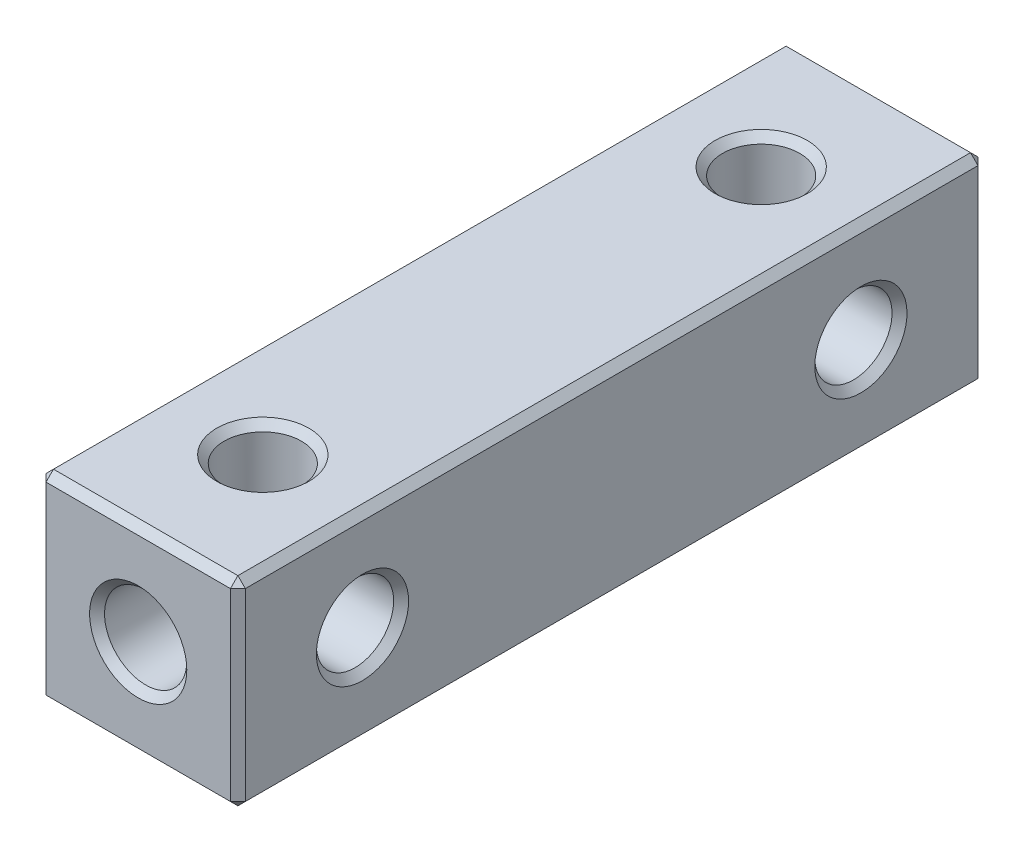
SolidWorks part; units mm, degrees
ref_plane "前视基准面" through (0, 0, 0) normal (0, 0, 1) x (1, 0, 0)
ref_plane "上视基准面" through (0, 0, 0) normal (0, 1, 0) x (1, 0, 0)
ref_plane "右视基准面" through (0, 0, 0) normal (1, 0, 0) x (0, 0, -1)
sketch "草图1" plane through (0, 0, 0) normal (0, 0, 1) x (1, 0, 0)
  line L1 (-4, 4) -> (4, 4)
  line L2 (-4, 4) -> (-4, -4)
  line L3 (-4, -4) -> (4, -4)
  line L4 (4, 4) -> (4, -4)
  line L5 (-4, 4) -> (4, -4) construction
  line L6 (-4, -4) -> (4, 4) construction
  point P0 (0, 0)
  dimension "D1" = 8
extrude "凸台-拉伸1" add sketch "草图1" along normal mid plane 30
hole_wizard "Ø3.1 (3.1) 直径孔1" positions "草图2" profile "草图3" hole size "Ø3.1" standard "GB" end condition through all
sketch "草图2" plane through (4, 0, 0) normal (1, 0, 0) x (0, 0, -1)
  line L0 (0, 0) -> (0, 50000) construction
  line L1 (-15, 4) -> (15, 4) construction
  line L2 (0, 0) -> (50000, 0) construction
  point P0 (-10, 0)
  point P2 (10, 0)
  point P10 (0, 4)
  point P15 (0, 0)
  point P16 (0, 0)
  dimension "D1" = 20
sketch "草图3" plane through (4, 0, 10) normal (0, 1, 0) x (0, 0, -1)
  line L0 (0, 0) -> (0, 8)
  line L1 (0, 8) -> (1.55, 8)
  line L2 (1.55, 8) -> (1.55, 0)
  line L5 (1.55, 0) -> (0, 0)
  line L11 (0, -6.35) -> (0, 107.95) construction
  dimension "通孔孔直径" = 3.1
  dimension "通孔孔深度" = 8
hole_wizard "Ø3.1 (3.1) 直径孔2" positions "草图4" profile "草图5" hole size "Ø3.1" standard "GB" end condition through all
sketch "草图4" plane through (0, 4, 0) normal (0, 1, 0) x (1, 0, 0)
  line L0 (0, 0) -> (0, 50000) construction
  line L1 (0, 0) -> (-50000, 0) construction
  point P0 (0, -10)
  point P2 (0, 10)
  point P9 (0, 0)
  point P10 (0, 0)
  point P11 (0, 0)
  dimension "D1" = 20
sketch "草图5" plane through (0, 4, 10) normal (1, 0, 0) x (0, 0, 1)
  line L0 (0, 0) -> (0, 8)
  line L1 (0, 8) -> (1.55, 8)
  line L2 (1.55, 8) -> (1.55, 0)
  line L5 (1.55, 0) -> (0, 0)
  line L11 (0, -6.35) -> (0, 107.95) construction
  dimension "通孔孔直径" = 3.1
  dimension "通孔孔深度" = 8
hole_wizard "M4 螺纹孔1" positions "草图6" profile "草图7" tap size "M4" standard "GB"
sketch "草图6" plane through (0, 0, 15) normal (0, 0, 1) x (1, 0, 0)
  point P0 (0, 0)
sketch "草图7" plane through (0, 0, 15) normal (1, 0, 0) x (0, -1, 0)
  line L0 (0, 0) -> (0, 3.45)
  line L1 (0, 3.45) -> (1.65, 3.45)
  line L2 (1.65, 3.45) -> (1.65, 0)
  line L5 (1.65, 0) -> (0, 0)
  line L11 (0, -6.35) -> (0, 107.95) construction
  dimension "通孔螺纹孔钻头直径" = 3.3
  dimension "通孔螺纹孔钻头深度" = 3.45
cosmetic thread "孔螺蚊线1" parameters "D2"=4
hole_wizard "M4 螺纹孔2" positions "草图8" profile "草图9" tap size "M4" standard "GB"
sketch "草图8" plane through (0, 0, -15) normal (0, 0, -1) x (-1, 0, 0)
  point P0 (0, 0)
sketch "草图9" plane through (0, 0, -15) normal (1, 0, 0) x (0, 1, 0)
  line L0 (0, 0) -> (0, 3.45)
  line L1 (0, 3.45) -> (1.65, 3.45)
  line L2 (1.65, 3.45) -> (1.65, 0)
  line L5 (1.65, 0) -> (0, 0)
  line L11 (0, -6.35) -> (0, 107.95) construction
  dimension "通孔螺纹孔钻头直径" = 3.3
  dimension "通孔螺纹孔钻头深度" = 3.45
cosmetic thread "孔螺蚊线2" parameters "D2"=4
chamfer "倒角1" distance 0.3 angle 45 22 edges at (-1.65, 0, -15) (1.65, 0, 15) (4, 0, -11.55) (4, 0, 8.45) (0, -4, -8.45) (0, -4, 11.55) (-4, 0, -11.55) (-4, 0, 8.45) (4, 0, 15) (4, 0, -15) (0, -4, 15) (4, -4, 0) (0, -4, -15) (-4, 0, 15) (-4, -4, 0) (-4, 0, -15) (4, 4, 0) (0, 4, 15) (-4, 4, 0) (0, 4, -15) (0, 4, -8.45) (0, 4, 11.55)
